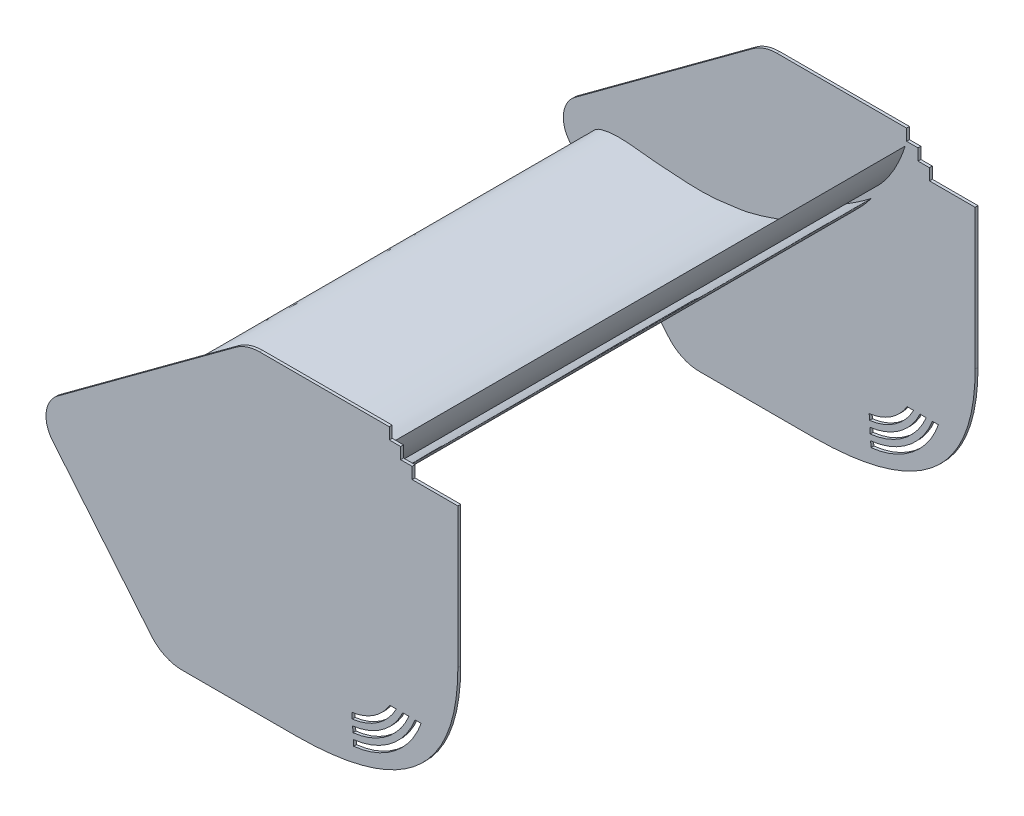
SolidWorks part; units mm, degrees
ref_plane "Front Plane" through (0, 0, 0) normal (0, 0, 1) x (1, 0, 0)
ref_plane "Top Plane" through (0, 0, 0) normal (0, 1, 0) x (1, 0, 0)
ref_plane "Right Plane" through (0, 0, 0) normal (1, 0, 0) x (0, 0, -1)
sketch "Sketch1" plane through (0, 0, 0) normal (0, 0, 1) x (1, 0, 0)
  line L0 (46.9575, 64.3181) -> (1074.8558, 208.7798) construction
sketch "Sketch2" plane through (0, 0, 0) normal (0, 0, 1) x (1, 0, 0)
  line L0 (0, 0) -> (400, 0) construction
  line L1 (0, 0) -> (399.6225, 66.8739) construction
  line L2 (0, 66.8739) -> (0, -66.8739) construction
  line L3 (10.0115, 66.8739) -> (10.0115, -116.1581) construction
  line L4 (20.0229, 66.8739) -> (20.0229, -116.1581) construction
  line L5 (30.0344, 66.8739) -> (30.0344, -116.1581) construction
  line L6 (40.0459, 66.8739) -> (40.0459, -116.1581) construction
  line L7 (50.0573, 66.8739) -> (50.0573, -116.1581) construction
  line L8 (60.0688, 66.8739) -> (60.0688, -116.1581) construction
  line L9 (70.0803, 66.8739) -> (70.0803, -116.1581) construction
  line L10 (80.0918, 66.8739) -> (80.0918, -116.1581) construction
  line L11 (90.1032, 66.8739) -> (90.1032, -116.1581) construction
  line L12 (100.1147, 66.8739) -> (100.1147, -116.1581) construction
  line L13 (110.1262, 66.8739) -> (110.1262, -116.1581) construction
  line L14 (120.1376, 66.8739) -> (120.1376, -116.1581) construction
  line L15 (130.1491, 66.8739) -> (130.1491, -116.1581) construction
  line L16 (140.1606, 66.8739) -> (140.1606, -116.1581) construction
  line L17 (150.172, 66.8739) -> (150.172, -116.1581) construction
  line L18 (160.1835, 66.8739) -> (160.1835, -116.1581) construction
  line L19 (170.195, 66.8739) -> (170.195, -116.1581) construction
  line L20 (180.2064, 66.8739) -> (180.2064, -116.1581) construction
  line L21 (190.2179, 66.8739) -> (190.2179, -116.1581) construction
  line L22 (200.2294, 66.8739) -> (200.2294, -116.1581) construction
  line L23 (210.2408, 66.8739) -> (210.2408, -116.1581) construction
  line L24 (220.2523, 66.8739) -> (220.2523, -116.1581) construction
  line L25 (230.2638, 66.8739) -> (230.2638, -116.1581) construction
  line L26 (240.2753, 66.8739) -> (240.2753, -116.1581) construction
  line L27 (250.2867, 66.8739) -> (250.2867, -116.1581) construction
  line L28 (260.2982, 66.8739) -> (260.2982, -116.1581) construction
  line L29 (270.3097, 66.8739) -> (270.3097, -116.1581) construction
  line L30 (280.3211, 66.8739) -> (280.3211, -116.1581) construction
  line L31 (290.3326, 66.8739) -> (290.3326, -116.1581) construction
  line L32 (300.3441, 66.8739) -> (300.3441, -116.1581) construction
  line L33 (310.3555, 66.8739) -> (310.3555, -116.1581) construction
  line L34 (320.367, 66.8739) -> (320.367, -116.1581) construction
  line L35 (330.3785, 66.8739) -> (330.3785, -116.1581) construction
  line L36 (340.3899, 66.8739) -> (340.3899, -116.1581) construction
  line L37 (350.4014, 66.8739) -> (350.4014, -116.1581) construction
  line L38 (360.4129, 66.8739) -> (360.4129, -116.1581) construction
  line L39 (370.4243, 66.8739) -> (370.4243, -116.1581) construction
  line L40 (380.4358, 66.8739) -> (380.4358, -116.1581) construction
  line L41 (390.4473, 66.8739) -> (390.4473, -116.1581) construction
  line L42 (400.4588, 66.8739) -> (400.4588, -116.1581) construction
  line L43 (836.1007, 66.8739) -> (-36.8556, 66.8739) construction
  line L44 (389.6225, 76.8739) -> (409.6225, 76.8739) construction
  line L45 (399.6225, 90.7703) -> (399.6225, 62.9774) construction
  line L46 (548.1427, 255.362) -> (478.7399, 156.2446) construction
  line L47 (488.7399, 146.2766) -> (482.6971, 142.1346) construction
  line L48 (389.6225, 76.8739) -> (488.7399, 146.2766) construction
  line L51 (488.7399, 194.8045) -> (488.7399, 123.7678) construction
  line L52 (478.7399, 201.6203) -> (478.7399, 116.9521) construction
  line L53 (478.7399, 156.2446) -> (614.5057, 156.2446) construction
  line L54 (389.6225, 83.3039) -> (389.6225, -27.4023) construction
  line L55 (478.7399, 146.2446) -> (614.5057, 146.2446) construction
  spline S0 degree 3 poles (8.4176, 12.2629) (-5.1, -0.6947) (8.0175, -15.4806) (19.5512, -21.724) (30.0167, -25.3022) (39.86, -28.8642) (50.0404, -30.6629) (60.0706, -32.2577) (70.0139, -34.2177) (80.101, -34.56) (90.0931, -35.3652) (100.112, -35.9529) (110.1282, -35.5072) (120.1532, -35.21) (130.1503, -34.2298) (140.19, -33.4102) (150.1782, -31.9134) (160.1704, -30.3713) (170.2408, -29.1636) (180.2083, -27.151) (190.2638, -25.3061) (200.2392, -22.8725) (210.2446, -20.4291) (220.2329, -17.8951) (230.3811, -15.7054) (240.3519, -12.3911) (253.5512, -7.3696) (266.9476, -2.8065) (280.4369, 1.6366) (290.3614, 5.8195) (300.4407, 10.0322) (310.3048, 14.8841) (323.8214, 20.8842) (337.3023, 27.2498) (350.2747, 34.8502) (364.0374, 41.2007) (378.0734, 50.4319) (389.2687, 56.9917) (404.9331, 70.6704) (388.8931, 60.8973) (380.9617, 56.8333) (370.3166, 52.1732) (360.4136, 47.7491) (350.4697, 43.0754) (340.4967, 38.8332) (330.4052, 35.261) (320.3498, 31.8494) (310.3583, 28.3259) (300.4869, 24.6622) (290.3218, 22.3006) (280.2904, 19.7619) (270.4267, 16.765) (260.336, 15.0613) (250.2769, 13.9588) (240.2662, 12.5783) (230.2787, 11.0679) (220.2867, 9.6964) (210.2433, 9.2404) (200.2287, 9.0345) (190.217, 8.2792) (180.2125, 9.1624) (170.1842, 8.7285) (160.1865, 9.5822) (150.1678, 9.9892) (140.1635, 10.7007) (130.146, 11.2145) (120.1214, 11.8409) (110.1328, 12.9697) (100.1148, 13.8501) (90.0938, 14.7159) (80.0796, 15.8427) (56.9177, 18.8475) (32.3828, 18.9634) (8.4176, 12.2629) (-5.1, -0.6947) (8.0175, -15.4806) knots -0.089629 -0.030705 -0.018228 0 0.022024 0.035622 0.048197 0.060585 0.072602 0.084545 0.096479 0.108284 0.12009 0.131879 0.143661 0.155449 0.167269 0.1791 0.190991 0.202897 0.214788 0.226766 0.238768 0.250864 0.262992 0.27512 0.287235 0.299601 0.31215 0.337082 0.349542 0.362249 0.375072 0.388091 0.40103 0.427261 0.440709 0.453892 0.481344 0.495528 0.510184 0.522428 0.535733 0.548643 0.561554 0.574511 0.587287 0.599816 0.612271 0.624763 0.637218 0.649381 0.661544 0.67375 0.685718 0.697586 0.709472 0.721375 0.733243 0.74504 0.756824 0.768611 0.780398 0.792175 0.803972 0.815766 0.827567 0.839363 0.851169 0.863006 0.874833 0.88666 0.89851 0.910371 0.969295 0.981772 1 1.022024 1.035622 1.048197 only from (0, 0) to (0, 0)
  spline S1 degree 3 poles (488.4807, 145.9571) (488.8121, 146.3498) (488.4243, 146.015) (488.0622, 145.7851) (487.2625, 145.1263) (486.2197, 144.3713) (484.8735, 143.3367) (483.2507, 142.1161) (481.3449, 140.7026) (479.1839, 139.1083) (476.7613, 137.3643) (474.1237, 135.4494) (471.2368, 133.4393) (468.1657, 131.2913) (464.8962, 129.0676) (461.4575, 126.7695) (457.874, 124.4106) (454.1513, 122.027) (450.3296, 119.6083) (446.4184, 117.1921) (442.4423, 114.7926) (438.4319, 112.4153) (434.4211, 110.0589) (430.4193, 107.7484) (426.4691, 105.4752) (422.5724, 103.27) (418.7829, 101.1054) (415.1038, 99.0189) (411.5811, 96.98) (408.2231, 95.0247) (405.0701, 93.1172) (402.1178, 91.3128) (399.4157, 89.5543) (396.9653, 87.8935) (394.7924, 86.3186) (392.9158, 84.83) (391.3498, 83.4309) (390.0835, 82.1509) (389.1526, 80.9646) (388.5665, 79.872) (388.3105, 78.8689) (388.4525, 77.9475) (389.0134, 77.2045) (389.9156, 76.685) (391.1282, 76.3842) (392.6501, 76.2546) (394.4851, 76.3138) (396.6232, 76.5794) (399.0459, 77.0357) (401.7358, 77.7205) (404.6757, 78.5968) (407.8392, 79.7049) (411.2008, 81.0269) (414.7209, 82.591) (418.3956, 84.3418) (422.1799, 86.3091) (426.0457, 88.48) (429.9704, 90.8288) (433.915, 93.3645) (437.8712, 96.0402) (441.7934, 98.8661) (445.6685, 101.7972) (449.4657, 104.8272) (453.1679, 107.924) (456.7615, 111.054) (460.2029, 114.2195) (463.5191, 117.343) (466.6501, 120.455) (469.6136, 123.4898) (472.3702, 126.4509) (474.954, 129.2656) (477.2978, 131.9605) (479.4562, 134.4635) (481.3811, 136.7846) (483.0779, 138.8974) (484.5577, 140.7696) (485.8099, 142.3825) (486.8479, 143.7389) (487.6258, 144.7686) (488.2511, 145.5957) (488.4807, 145.9571) (488.8121, 146.3498) (488.4243, 146.015) knots -0.00692 -0.003098 -0.00077 0 0.000781 0.003074 0.006931 0.012248 0.01903 0.027226 0.036785 0.04761 0.059602 0.072764 0.086897 0.102004 0.117939 0.134556 0.151858 0.169651 0.187838 0.206374 0.225065 0.243814 0.262569 0.281137 0.299514 0.317506 0.335105 0.352118 0.368488 0.384167 0.398955 0.412906 0.425872 0.437811 0.448585 0.458213 0.466669 0.473884 0.479894 0.484779 0.488743 0.492167 0.495628 0.499576 0.504487 0.510576 0.517943 0.526574 0.536524 0.54764 0.560015 0.573491 0.588031 0.603544 0.619912 0.637089 0.654944 0.673346 0.692212 0.711461 0.73091 0.750475 0.770022 0.789461 0.808651 0.827458 0.84582 0.863559 0.880666 0.896945 0.912322 0.926718 0.939993 0.952161 0.96306 0.972662 0.980906 0.987733 0.99308 0.996902 0.99923 1 1.000781 1.003074 1.006931 only from (488.7399, 146.2766) to (488.7399, 146.2766)
  spline S2 degree 3 poles (548.0012, 254.9703) (548.1874, 255.456) (547.9279, 255.0069) (547.6584, 254.6667) (547.113, 253.7707) (546.3674, 252.702) (545.4246, 251.265) (544.2794, 249.5582) (542.9279, 247.5728) (541.3924, 245.3297) (539.6567, 242.8564) (537.7725, 240.1482) (535.6814, 237.266) (533.4602, 234.1907) (531.0746, 230.977) (528.5519, 227.6359) (525.9111, 224.1885) (523.1453, 220.6711) (520.2967, 217.0873) (517.3615, 213.4761) (514.3589, 209.8593) (511.316, 206.2523) (508.2658, 202.665) (505.209, 199.1247) (502.189, 195.6372) (499.1976, 192.2326) (496.2952, 188.9024) (493.4722, 185.6835) (490.783, 182.5623) (488.2235, 179.5757) (485.844, 176.7031) (483.6219, 173.9957) (481.6239, 171.4156) (479.834, 169.0126) (478.2807, 166.784) (476.9821, 164.7365) (475.9505, 162.878) (475.1658, 161.233) (474.6707, 159.7892) (474.4739, 158.5497) (474.5629, 157.5056) (475.0053, 156.672) (475.7887, 156.1483) (476.824, 155.9518) (478.0833, 156.0678) (479.5813, 156.4503) (481.3159, 157.1174) (483.2715, 158.0828) (485.4358, 159.3251) (487.7794, 160.8747) (490.2983, 162.6906) (492.9538, 164.8026) (495.7276, 167.1848) (498.5723, 169.8513) (501.5026, 172.7478) (504.4658, 175.8877) (507.4391, 179.2493) (510.4095, 182.8005) (513.3367, 186.5371) (516.2285, 190.4114) (519.0377, 194.4179) (521.767, 198.5093) (524.3889, 202.6695) (526.8977, 206.8618) (529.2916, 211.0497) (531.5283, 215.2209) (533.6592, 219.3103) (535.617, 223.3271) (537.4402, 227.2144) (539.0902, 230.9623) (540.6237, 234.5128) (541.9677, 237.8689) (543.1982, 240.9799) (544.2661, 243.8393) (545.1852, 246.4237) (545.977, 248.7058) (546.6373, 250.6644) (547.1783, 252.3065) (547.5794, 253.5497) (547.9019, 254.5484) (548.0012, 254.9703) (548.1874, 255.456) (547.9279, 255.0069) knots -0.00692 -0.003098 -0.00077 0 0.000781 0.003074 0.006931 0.012248 0.01903 0.027226 0.036785 0.04761 0.059602 0.072764 0.086897 0.102004 0.117939 0.134556 0.151858 0.169651 0.187838 0.206374 0.225065 0.243814 0.262569 0.281137 0.299514 0.317506 0.335105 0.352118 0.368488 0.384167 0.398955 0.412906 0.425872 0.437811 0.448585 0.458213 0.466669 0.473884 0.479894 0.484779 0.488743 0.492167 0.495628 0.499576 0.504487 0.510576 0.517943 0.526574 0.536524 0.54764 0.560015 0.573491 0.588031 0.603544 0.619912 0.637089 0.654944 0.673346 0.692212 0.711461 0.73091 0.750475 0.770022 0.789461 0.808651 0.827458 0.84582 0.863559 0.880666 0.896945 0.912322 0.926718 0.939993 0.952161 0.96306 0.972662 0.980906 0.987733 0.99308 0.996902 0.99923 1 1.000781 1.003074 1.006931 only from (548.1427, 255.362) to (548.1427, 255.362)
  point P7 (0, 0)
  point P94 (399.6225, 76.8739)
  point P100 (399.6225, 76.8739)
  point P108 (399.6225, 66.8739)
  point P112 (389.6225, 76.8739)
  point P126 (488.7399, 146.2766)
  point P130 (488.7399, 156.2766)
  point P136 (488.7399, 159.2862)
  point P142 (478.7399, 159.2862)
  dimension "D1" = 9.5
  dimension "D3" = 405.1793
  dimension "D4" = 400
  dimension "D5" = 121
  dimension "D6" = 10
  dimension "D7" = 35
  dimension "D8" = 10
  dimension "D9" = 55
  dimension "D10" = 10
  dimension "D11" = 121
  dimension "D12" = 10
  dimension "D13" = 79.3707
  dimension "D2" = 41
extrude "Boss-Extrude1" add sketch "Sketch2" along normal blind 900
ref_plane "Plane1" through (0, 0, 900) normal (0, 0, 1) x (1, 0, 0)
sketch "Sketch3" plane through (0, 0, 900) normal (0, 0, 1) x (1, 0, 0)
  line L0 (550.5292, 283.8431) -> (550.5292, 263.8431) construction
  line L1 (458.9571, 283.8431) -> (550.5292, 283.8431)
  line L4 (670.5292, 223.8431) -> (670.5292, -21.1569)
  line L14 (458.9571, 283.8431) -> (323.8067, 283.8431)
  line L15 (-38.5344, -31.8606) -> (134.1866, -240.7617)
  line L20 (670.5292, -21.1569) -> (670.5292, -264.5989) construction
  line L21 (670.5292, -264.5989) -> (389.1355, -266.1569) construction
  line L26 (-29.6676, 40.2471) -> (282.2721, 270.1891)
  line L29 (670.5292, 223.8431) -> (590.5292, 223.8431)
  line L30 (550.5292, 263.8431) -> (550.5292, 283.8431)
  line L31 (550.5292, 263.8431) -> (570.5292, 263.8431)
  line L32 (570.5292, 263.8431) -> (570.5292, 243.8431)
  line L33 (570.5292, 243.8431) -> (590.5292, 243.8431)
  line L34 (590.5292, 243.8431) -> (590.5292, 223.8431)
  line L35 (188.1348, -266.1569) -> (389.1355, -266.1569)
  line L38 (550.5292, 283.8431) -> (550.5292, -265.2633) construction
  arc A3 (-29.6676, 40.2471) -> (-38.5344, -31.8606) centre (0, 0) ccw
  arc A4 (134.1866, -240.7617) -> (188.1348, -266.1569) centre (188.1348, -196.1569) ccw
  arc A5 (282.2721, 270.1891) -> (323.8067, 283.8431) centre (323.8067, 213.8431) cw
  spline S2 degree 2 poles (670.5292, -21.1569) (670.5292, -264.5989) (389.1355, -266.1569) knots 0 0 0 1 1 1
  point P19 (300.7951, 283.8431)
  dimension "D4" = 20
  dimension "D2" = 100
  dimension "D5" = 20
  dimension "D10" = 70
  dimension "D11" = 70
  dimension "D1" = 550
  dimension "D3" = 120
  dimension "D6" = 20
  dimension "D7" = 249.7341
  dimension "D8" = 20
  dimension "D9" = 20
extrude "Boss-Extrude2" add sketch "Sketch3" along normal blind 5
ref_plane "Plane2" through (0, 0, 450) normal (0, 0, 1) x (1, 0, 0)
sketch "Sketch11" plane through (0, 0, 900) normal (0, 0, -1) x (-1, 0, 0)
  line L1 (-488.3144, -231.425) -> (-487.6766, -221.4355)
  line L3 (-485.7625, -191.4551) -> (-485.1241, -181.4556)
  line L4 (-487.0387, -211.4443) -> (-486.4007, -201.4511)
  line L5 (-606.2745, -137.7639) -> (-595.6356, -137.7639)
  line L6 (-562.8391, -137.7639) -> (-551.4085, -137.7639)
  line L7 (-584.8785, -137.7639) -> (-573.9653, -137.7639)
  arc A0 (-595.6356, -137.7639) -> (-487.6766, -221.4355) centre (-473.345, -91.4598) ccw
  arc A1 (-606.2745, -137.7639) -> (-488.3144, -231.425) centre (-473.345, -91.4598) ccw
  arc A2 (-603.9559, -85.1463) -> (-487.251, -221.4817) centre (-473.345, -91.4598) ccw construction
  arc A3 (-613.9442, -84.6635) -> (-488.3144, -231.425) centre (-473.345, -91.4598) ccw construction
  arc A4 (-584.8785, -137.7639) -> (-487.0387, -211.4443) centre (-473.345, -91.4598) ccw
  arc A5 (-573.9653, -137.7639) -> (-486.4007, -201.4511) centre (-473.345, -91.4598) ccw
  arc A6 (-562.8391, -137.7639) -> (-485.7625, -191.4551) centre (-473.345, -91.4598) ccw
  arc A7 (-551.4085, -137.7639) -> (-485.1241, -181.4556) centre (-473.345, -91.4598) ccw
  arc A8 (-559.0571, -121.3164) -> (-482.9972, -181.7085) centre (-473.345, -91.4598) ccw construction
  arc A9 (-568.5006, -124.6059) -> (-484.0606, -191.6518) centre (-473.345, -91.4598) ccw construction
  arc A10 (-577.9441, -127.8954) -> (-485.1241, -201.5951) centre (-473.345, -91.4598) ccw construction
  arc A11 (-587.3876, -131.1849) -> (-486.1875, -211.5384) centre (-473.345, -91.4598) ccw construction
  dimension "D2" = 140.7634
  dimension "D1" = 10
  dimension "D3" = 20
  dimension "D4" = 10
  dimension "D5" = 10
  dimension "D6" = 10
extrude "Cut-Extrude13" cut sketch "Sketch11" against normal blind 10
mirror "Mirror2" about plane through (0, 0, 450) normal (0, 0, 1) of "Cut-Extrude13", "Boss-Extrude2"
